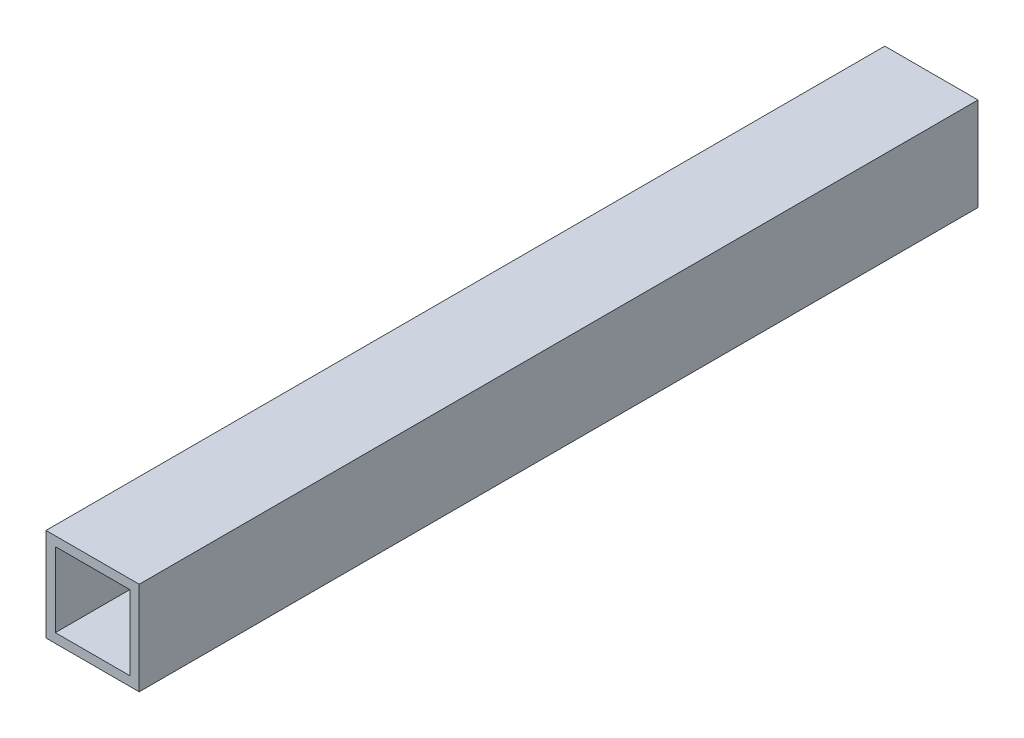
SolidWorks part; units mm, degrees
ref_plane "Front Plane" through (0, 0, 0) normal (0, 0, 1) x (1, 0, 0)
ref_plane "Top Plane" through (0, 0, 0) normal (0, 1, 0) x (1, 0, 0)
ref_plane "Right Plane" through (0, 0, 0) normal (1, 0, 0) x (0, 0, -1)
sketch "Sketch2" plane through (0, 0, 0) normal (0, 0, 1) x (1, 0, 0)
  line L0 (-10.16, 10.16) -> (10.16, 10.16)
  line L1 (-12.7, -12.7) -> (12.7, -12.7)
  line L2 (-12.7, -12.7) -> (-12.7, 12.7)
  line L3 (-12.7, 12.7) -> (12.7, 12.7)
  line L4 (12.7, -12.7) -> (12.7, 12.7)
  line L5 (-12.7, -12.7) -> (12.7, 12.7) construction
  line L6 (-12.7, 12.7) -> (12.7, -12.7) construction
  line L7 (10.16, -10.16) -> (10.16, 10.16)
  line L8 (-10.16, -10.16) -> (10.16, -10.16)
  line L9 (-10.16, -10.16) -> (-10.16, 10.16)
  point P0 (0, 0)
  dimension "D1" = 25.4
  dimension "D2" = 25.4
  dimension "D3" = 2.54
extrude "Boss-Extrude1" add sketch "Sketch2" along normal blind 228.6
